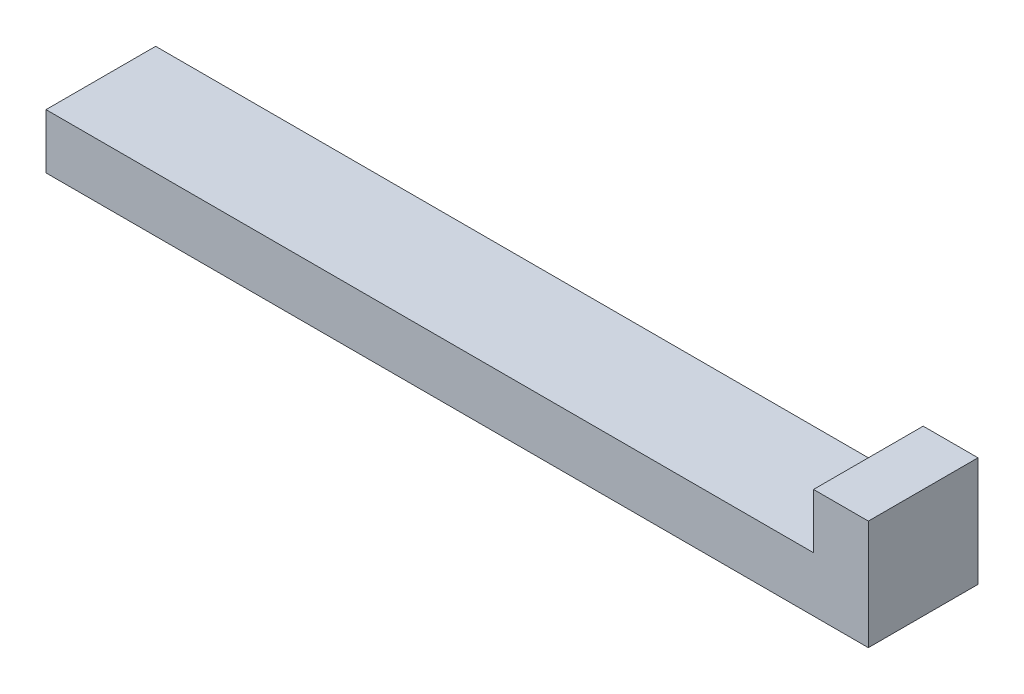
SolidWorks part; units mm, degrees
ref_plane "前视基准面" through (0, 0, 0) normal (0, 0, 1) x (1, 0, 0)
ref_plane "上视基准面" through (0, 0, 0) normal (0, 1, 0) x (1, 0, 0)
ref_plane "右视基准面" through (0, 0, 0) normal (1, 0, 0) x (0, 0, -1)
sketch "草图1" plane through (0, 0, 0) normal (0, 0, 1) x (1, 0, 0)
  line L0 (0, 0) -> (15, 0)
  line L1 (15, 0) -> (15, 2)
  line L2 (15, 2) -> (14, 2)
  line L3 (14, 2) -> (14, 1)
  line L4 (14, 1) -> (0, 1)
  line L5 (0, 1) -> (0, 0)
extrude "凸台-拉伸1" add sketch "草图1" along normal blind 2
